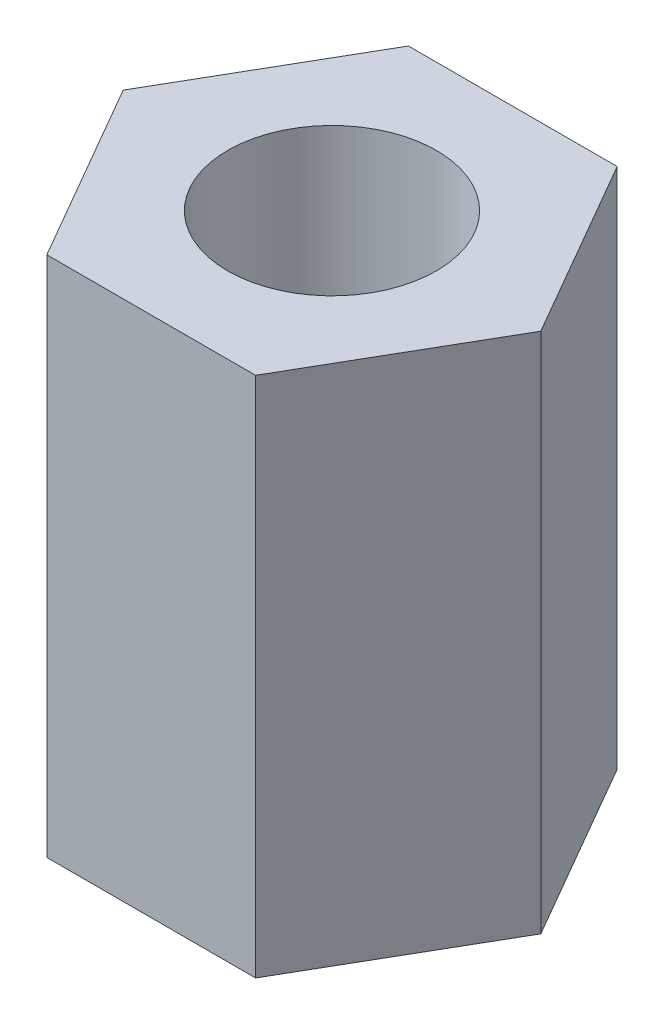
SolidWorks part; units mm, degrees
ref_plane "前视基准面" through (0, 0, 0) normal (0, 0, 1) x (1, 0, 0)
ref_plane "上视基准面" through (0, 0, 0) normal (0, 1, 0) x (1, 0, 0)
ref_plane "右视基准面" through (0, 0, 0) normal (1, 0, 0) x (0, 0, -1)
other "Configuration Table"
sketch "草图1" plane through (0, 0, 0) normal (0, 1, 0) x (1, 0, 0)
  line L1 (-6, 0) -> (-3, -5.1962)
  line L2 (-3, -5.1962) -> (3, -5.1962)
  line L3 (3, -5.1962) -> (6, 0)
  line L4 (6, 0) -> (3, 5.1962)
  line L5 (3, 5.1962) -> (-3, 5.1962)
  line L6 (-3, 5.1962) -> (-6, 0)
  circle A0 centre (0, 0) radius 5.1962 construction
  circle A1 centre (0, 0) radius 3
extrude "凸台-拉伸1" add sketch "草图1" along normal blind 15
